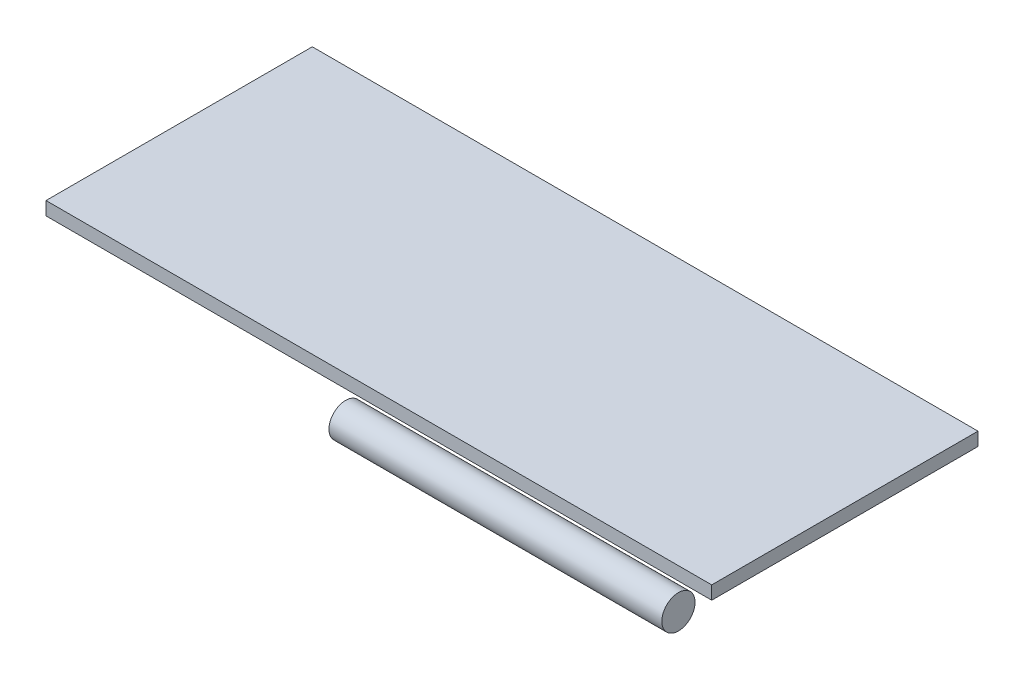
SolidWorks part; units mm, degrees
material "Hexcel AS4C (3000 Filaments)"
ref_plane "Front Plane" through (0, 0, 0) normal (0, 0, 1) x (1, 0, 0)
ref_plane "Top Plane" through (0, 0, 0) normal (0, 1, 0) x (1, 0, 0)
ref_plane "Right Plane" through (0, 0, 0) normal (1, 0, 0) x (0, 0, -1)
sketch "Sketch1" plane through (0, 0, 0) normal (0, 1, 0) x (1, 0, 0)
  line L1 (-50, -20) -> (50, -20)
  line L2 (-50, -20) -> (-50, 20)
  line L3 (-50, 20) -> (50, 20)
  line L4 (50, -20) -> (50, 20)
  line L5 (-50, -20) -> (50, 20) construction
  line L6 (-50, 20) -> (50, -20) construction
  point P0 (0, 0)
extrude "Boss-Extrude1" add sketch "Sketch1" along normal blind 2
sketch "Sketch2" plane through (50, 0, 0) normal (1, 0, 0) x (0, 0, -1)
  line L0 (-20, 1) -> (-25, 1)
  line L1 (-20, 2) -> (-20, 0) construction
  circle A0 centre (-25, 1) radius 2.5
extrude "Boss-Extrude2" add sketch "Sketch2" against normal blind 50 separate body contours A0
